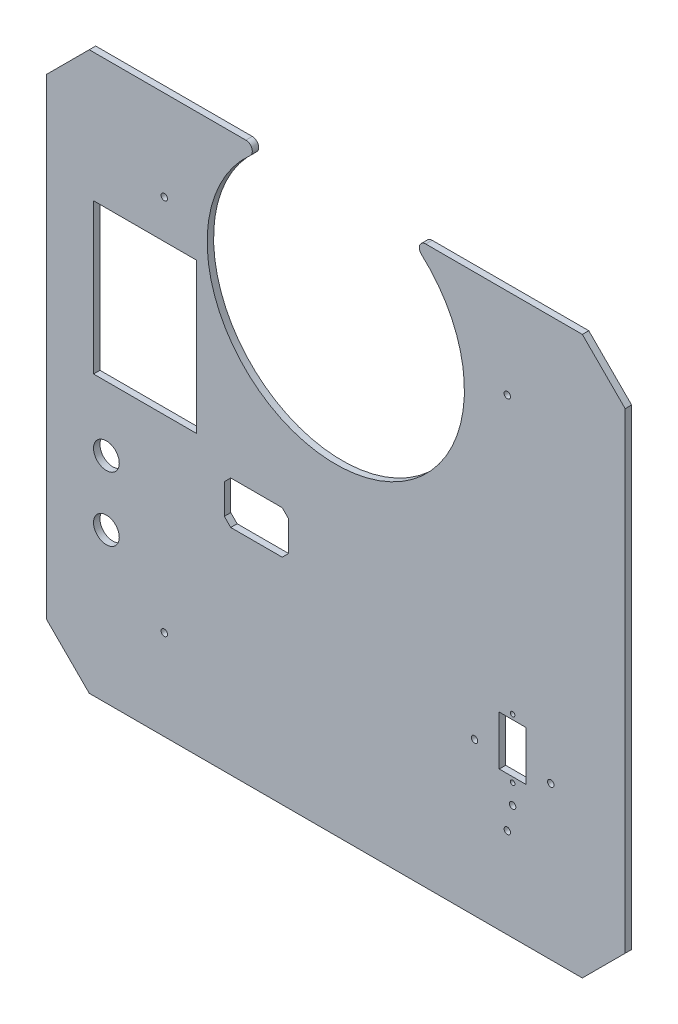
SolidWorks part; units mm, degrees
ref_plane "前视基准面" through (0, 0, 0) normal (0, 0, 1) x (1, 0, 0)
ref_plane "上视基准面" through (0, 0, 0) normal (0, 1, 0) x (1, 0, 0)
ref_plane "右视基准面" through (0, 0, 0) normal (1, 0, 0) x (0, 0, -1)
other "Configuration Table"
sketch "草图1" plane through (0, 0, 0) normal (0, 0, 1) x (1, 0, 0)
  line L1 (-135, -130) -> (135, -130)
  line L2 (-135, -130) -> (-135, 130)
  line L3 (-135, 130) -> (135, 130)
  line L4 (135, -130) -> (135, 130)
  line L5 (-135, -130) -> (135, 130) construction
  line L6 (-135, 130) -> (135, -130) construction
  point P0 (0, 0)
  dimension "D1" = 270
  dimension "D2" = 260
extrude "凸台-拉伸1" add sketch "草图1" along normal blind 3
sketch "草图2" plane through (0, 0, 3) normal (0, 0, 1) x (1, 0, 0)
  line L1 (135, 130) -> (-135, 130) construction
  line L4 (-50, 130) -> (50, 130)
  point P3 (0, 80)
  dimension "D1" = 100
chamfer "倒角2" distance 20 angle 45 4 edges at (-135, -130, 1.5) (135, -130, 1.5) (135, 130, 1.5) (-135, 130, 1.5)
sketch "草图3" plane through (0, 0, 3) normal (0, 0, 1) x (1, 0, 0)
  line L1 (88.75, -69.5) -> (76.25, -69.5)
  line L2 (88.75, -69.5) -> (88.75, -37.5)
  line L3 (88.75, -37.5) -> (76.25, -37.5)
  line L4 (76.25, -69.5) -> (76.25, -37.5)
sketch "草图4" plane through (0, 0, 3) normal (0, 0, 1) x (1, 0, 0)
  circle A0 centre (0, 80) radius 60
  dimension "D1" = 120
extrude "切除-拉伸1" cut sketch "草图4" against normal blind 10
fillet "圆角1" radius 3 2 edges at (-33.1662, 130, 1.5) (33.1662, 130, 1.5)
sketch "草图5" plane through (0, 0, 0) normal (0, 0, -1) x (-1, 0, 0)
  line L1 (-88.75, -41.9445) -> (-76.25, -41.9445)
  line L2 (-88.75, -41.9445) -> (-88.75, -64.9471)
  line L3 (-88.75, -64.9471) -> (-76.25, -64.9471)
  line L4 (-76.25, -41.9445) -> (-76.25, -64.9471)
  circle A0 centre (-64.7, -58.75) radius 1.5
  circle A1 centre (-100.3, -58.75) radius 1.5
  circle A2 centre (-82.5, -76.55) radius 1.5
  circle A3 centre (-82.5, -39.65) radius 1.05
  circle A4 centre (-82.5, -67.35) radius 1.05
  dimension "D1" = 2.1
  dimension "D2" = 2.1
extrude "切除-拉伸2" cut sketch "草图5" against normal blind 10
sketch "草图6" plane through (0, 0, 0) normal (0, 0, -1) x (-1, 0, 0)
  line L6 (65, 0) -> (113, 0)
  line L7 (65, 0) -> (65, 70)
  line L8 (65, 70) -> (113, 70)
  line L9 (113, 0) -> (113, 70)
extrude "切除-拉伸3" cut sketch "草图6" against normal blind 0.1
sketch "草图7" plane through (0, 0, 0) normal (0, 0, -1) x (-1, 0, 0)
  line L0 (65, 70) -> (113, 70) construction
  line L1 (65, 0) -> (115, 0)
  line L2 (65, 0) -> (65, 70)
  line L3 (65, 70) -> (115, 70)
  line L4 (115, 0) -> (115, 70)
sketch "草图8" plane through (0, 0, 3) normal (0, 0, 1) x (1, 0, 0)
  line L0 (-135, 110) -> (-135, -110) construction
  line L1 (-65, 70) -> (-113, 70) construction
  circle A0 centre (-107, 40) radius 6
  circle A1 centre (-107, 10) radius 6
  dimension "D1" = 28
  dimension "D2" = 28
  dimension "D3" = 12
  dimension "D4" = 12
  dimension "D5" = 30
  dimension "D6" = 30
sketch "草图10" plane through (0, 0, 0) normal (0, 0, -1) x (-1, 0, 0)
  line L0 (113, 0) -> (113, 70) construction
  line L1 (65, 70) -> (113, 70)
  line L2 (65, 70) -> (65, 0)
  line L3 (65, 0) -> (113, 0)
  line L4 (113, 70) -> (113, 0)
extrude "切除-拉伸4" cut sketch "草图10" against normal through all
sketch "草图11" plane through (0, 0, 3) normal (0, 0, 1) x (1, 0, 0)
  circle A0 centre (-107, -30) radius 6 construction
  circle A1 centre (-107, -30) radius 6
  circle A2 centre (-107, -60) radius 6 construction
  circle A3 centre (-107, -60) radius 6
extrude "切除-拉伸5" cut sketch "草图11" against normal through all
sketch "草图13" plane through (0, 0, 0) normal (0, 0, -1) x (-1, 0, 0)
  circle A0 centre (80, 88) radius 1.5
  circle A1 centre (80, -88) radius 1.5
  circle A2 centre (-80, -88) radius 1.5
  circle A3 centre (-80, 88) radius 1.5
extrude "切除-拉伸6" cut sketch "草图13" against normal through all
sketch "草图14" plane through (0, 0, 0) normal (0, 0, -1) x (-1, 0, 0)
  line L1 (-52, 10) -> (-12, 10)
  line L2 (-52, 10) -> (-52, -30)
  line L3 (-52, -30) -> (-12, -30)
  line L4 (-12, 10) -> (-12, -30)
  line L5 (-42, -30) -> (42, -30) construction
  line L6 (-52, 20) -> (-52, -20) construction
  dimension "D1" = 40
  dimension "D2" = 40
sketch "草图15" plane through (0, 0, 0) normal (0, 0, -1) x (-1, 0, 0)
  line L0 (-42, -30) -> (42, -30) construction
  line L1 (22, -30) -> (52, -30)
  line L2 (22, -30) -> (22, -10)
  line L3 (22, -10) -> (52, -10)
  line L4 (52, -30) -> (52, -10)
  line L5 (52, -20) -> (52, 20) construction
  dimension "D1" = 30
  dimension "D2" = 20
extrude "切除-拉伸8" cut sketch "草图15" against normal through all
chamfer "倒角4" distance 3 angle 45 4 edges at (-22, -10, 1.5) (-52, -10, 1.5) (-52, -30, 1.5) (-22, -30, 1.5)
